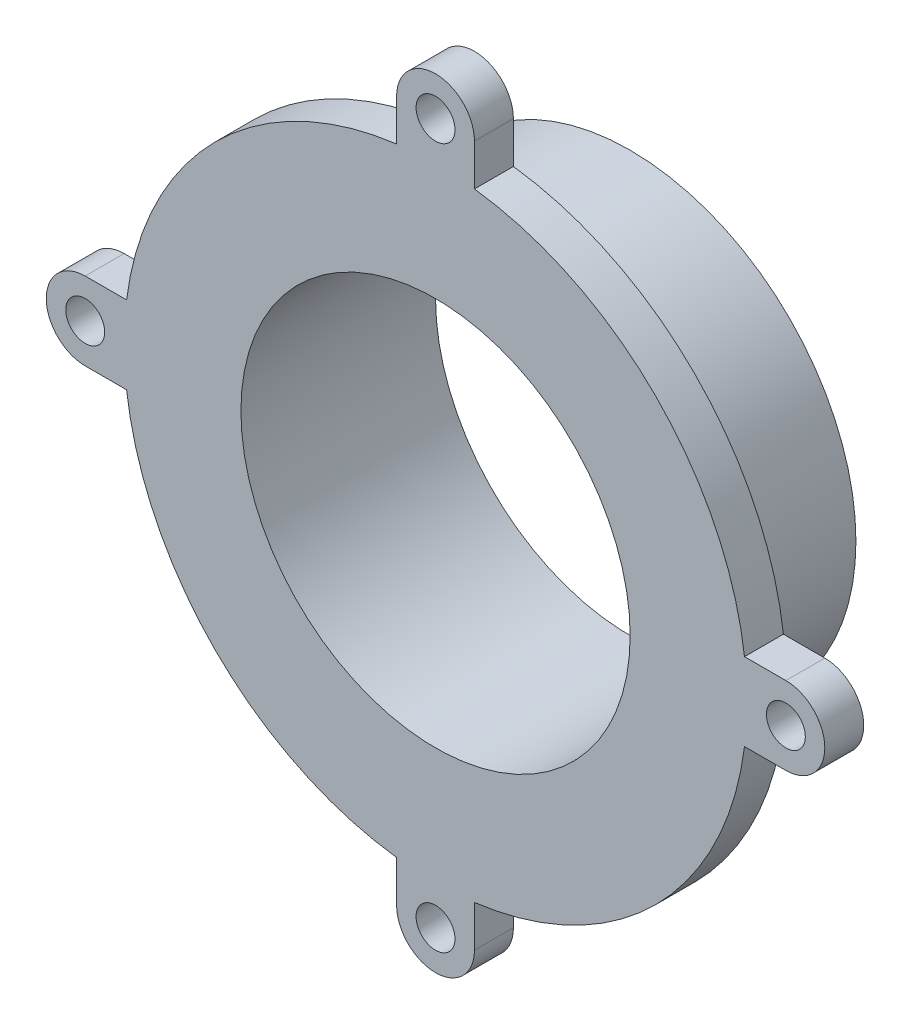
SolidWorks part; units mm, degrees
ref_plane "Front Plane" through (0, 0, 0) normal (0, 0, 1) x (1, 0, 0)
ref_plane "Top Plane" through (0, 0, 0) normal (0, 1, 0) x (1, 0, 0)
ref_plane "Right Plane" through (0, 0, 0) normal (1, 0, 0) x (0, 0, -1)
sketch "Sketch2" plane through (0, 0, 0) normal (0, 0, 1) x (1, 0, 0)
  circle A0 centre (0, 0) radius 40
  dimension "D1" = 80
extrude "Boss-Extrude2" add sketch "Sketch2" along normal blind 5
sketch "Sketch3" plane through (0, 0, 0) normal (0, 0, -1) x (-1, 0, 0)
  circle A0 centre (0, 0) radius 25
  dimension "D1" = 50
extrude "Cut-Extrude2" cut sketch "Sketch3" against normal blind 8
sketch "Sketch4" plane through (0, 0, 0) normal (0, 0, -1) x (-1, 0, 0)
  circle A0 centre (0, 0) radius 29
  circle A1 centre (0, 0) radius 25
  circle A2 centre (0, 0) radius 40
  circle A3 centre (0, 0) radius 40
  circle M3 centre (0, 0) radius 25
  dimension "D1" = 58
  dimension "D2" = 0
extrude "Boss-Extrude3" add sketch "Sketch4" along normal blind 20 contours A0 M3
sketch "Sketch5" plane through (0, 0, 5) normal (0, 0, 1) x (1, 0, 0)
  line L0 (0, 0) -> (0, 59.8577) construction
  line L1 (0, 0) -> (-5, 39.6863) construction
  line L2 (-5, 39.6863) -> (-5, 45)
  line L3 (5, 39.6863) -> (5, 45)
  circle A0 centre (0, 0) radius 40 construction
  arc A1 (-5, 45) -> (5, 45) centre (0, 45) cw
  arc A2 (5, 39.6863) -> (-5, 39.6863) centre (0, 0) ccw
  circle A3 centre (0, 45) radius 2.5
  dimension "D1" = 5
  dimension "D3" = 5
  dimension "D2" = 45
extrude "Boss-Extrude4" add sketch "Sketch5" against normal up to surface (5 mm away) up to face at (29, 0, 0)
pattern_circular "CirPattern1" count 4 every 90 about axis through (0, 0, 0) along (0, 0, 1) of "Boss-Extrude4"
